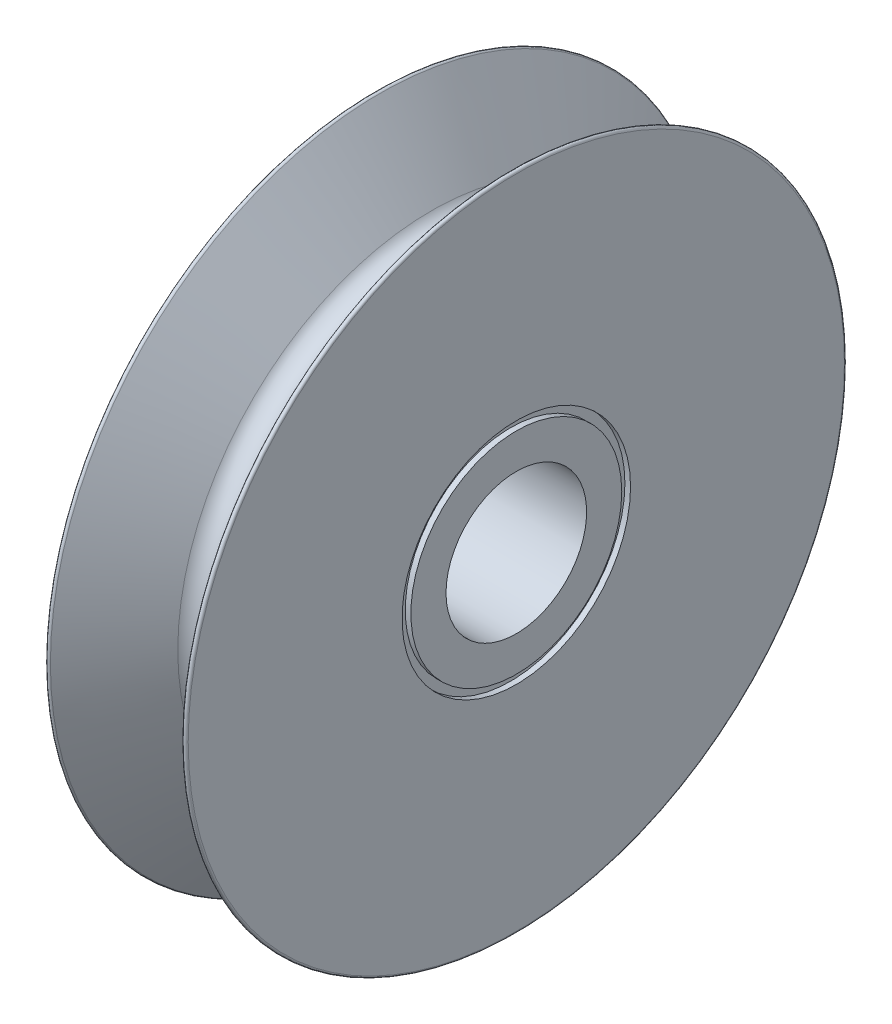
SolidWorks part; units mm, degrees
material "Plain Carbon Steel"
ref_plane "Front Plane" through (0, 0, 0) normal (0, 0, 1) x (1, 0, 0)
ref_plane "Top Plane" through (0, 0, 0) normal (0, 1, 0) x (1, 0, 0)
ref_plane "Right Plane" through (0, 0, 0) normal (1, 0, 0) x (0, 0, -1)
sketch "Sketch1" plane through (0, 0, 0) normal (0, 0, 1) x (1, 0, 0)
  line L0 (0, 0) -> (6.35, 0) construction
  line L1 (0, 3.175) -> (6.35, 3.175)
  line L2 (6.35, 3.175) -> (6.35, 14.8167)
  line L3 (6.1675, 14.8731) -> (3.83, 11.4579)
  line L4 (2.52, 11.4579) -> (0.1825, 14.8731)
  line L5 (0, 14.8167) -> (0, 3.175)
  line L6 (0, 3.175) -> (0, 0) construction
  line L7 (6.35, 3.175) -> (6.35, 0) construction
  line L8 (0, 11.1125) -> (6.35, 11.1125) construction
  arc A0 (3.83, 11.4579) -> (2.52, 11.4579) centre (3.175, 11.9062) cw
  arc A1 (6.35, 14.8167) -> (6.1675, 14.8731) centre (6.25, 14.8167) ccw
  arc A2 (0.1825, 14.8731) -> (0, 14.8167) centre (0.1, 14.8167) ccw
  dimension "D1" = 0.7937
  dimension "D3" = 0.1
  dimension "D2" = 6.35
  dimension "D4" = 29.6333
  dimension "D5" = 11.1125
  dimension "D6" = 6.35
revolve "Revolve1" add sketch "Sketch1" angle 360 about L0
sketch "Sketch4" plane through (6.35, 0, 0) normal (1, 0, 0) x (0, 0, -1)
  line L0 (0, 3.175) -> (0, 4.7625) construction
  line L1 (0, 4.7625) -> (0, 5.1594) construction
  line L2 (0, 5.1594) -> (0, 14.8167) construction
  line L3 (0, 3.175) -> (0, 0) construction
  circle A0 centre (0, 0) radius 4.7625
  circle A1 centre (0, 0) radius 5.1594
  circle A2 centre (0, 0) radius 3.175 construction
  circle A3 centre (0, 0) radius 14.8167 construction
  dimension "D1" = 1.5875
  dimension "D2" = 0.3969
extrude "Cut-Extrude1" cut sketch "Sketch4" against normal blind 0.254
sketch "Sketch5" plane through (0, 0, 0) normal (-1, 0, 0) x (0, 0, 1)
  line L0 (0, 2.3813) -> (0, 4.7625) construction
  line L1 (0, 4.7625) -> (0, 5.1594) construction
  line L2 (0, 5.1594) -> (0, 6.35) construction
  line L3 (0, 2.3813) -> (0, 0) construction
  circle A0 centre (0, 0) radius 4.7625
  circle A1 centre (0, 0) radius 5.1594
  circle A4 centre (0, 0) radius 4.7625 construction
  circle A5 centre (0, 0) radius 5.1594 construction
extrude "Cut-Extrude2" cut sketch "Sketch5" against normal blind 0.254
